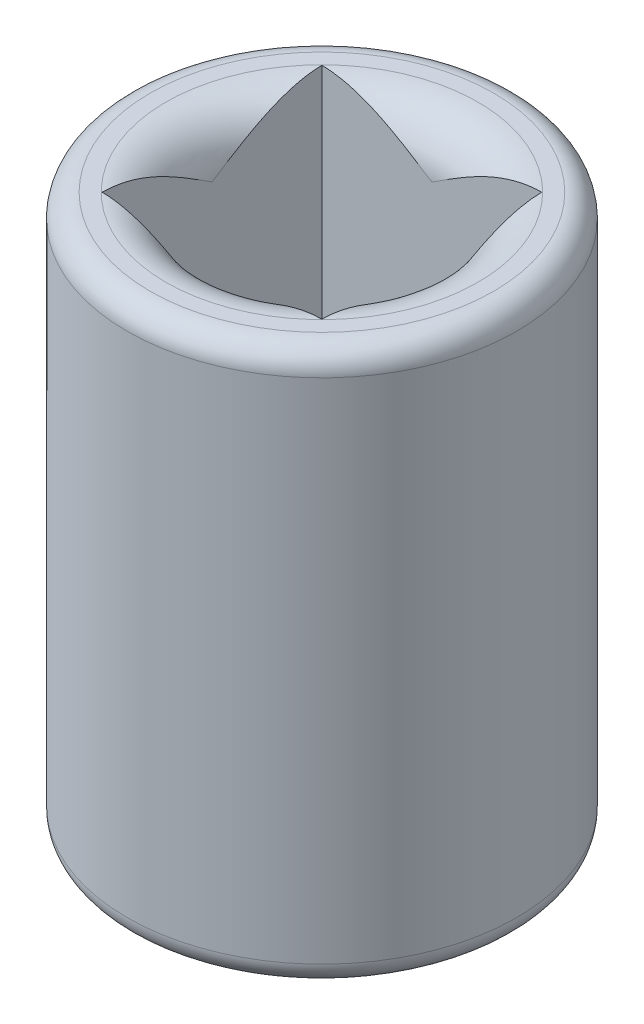
SolidWorks part; units mm, degrees
ref_plane "Front Plane" through (0, 0, 0) normal (0, 0, 1) x (1, 0, 0)
ref_plane "Top Plane" through (0, 0, 0) normal (0, 1, 0) x (1, 0, 0)
ref_plane "Right Plane" through (0, 0, 0) normal (1, 0, 0) x (0, 0, -1)
sketch "Sketch1" plane through (0, 0, 0) normal (0, 1, 0) x (1, 0, 0)
  circle A0 centre (0, 0) radius 8.44
  dimension "D1" = 16.88
extrude "Boss-Extrude1" add sketch "Sketch1" along normal blind 24
sketch "Sketch2" plane through (0, 24, 0) normal (0, 1, 0) x (1, 0, 0)
  line L1 (-4.7625, -4.7625) -> (4.7625, -4.7625)
  line L2 (-4.7625, -4.7625) -> (-4.7625, 4.7625)
  line L3 (-4.7625, 4.7625) -> (4.7625, 4.7625)
  line L4 (4.7625, -4.7625) -> (4.7625, 4.7625)
  line L5 (-4.7625, -4.7625) -> (4.7625, 4.7625) construction
  line L6 (-4.7625, 4.7625) -> (4.7625, -4.7625) construction
  point P0 (0, 0)
  dimension "D1" = 9.525
extrude "Cut-Extrude1" cut sketch "Sketch2" against normal blind 11.44
sketch "Sketch3" plane through (0, 12.56, 0) normal (0, 1, 0) x (1, 0, 0)
  circle A0 centre (0, 0) radius 4.5
  dimension "D1" = 9
extrude "Cut-Extrude2" cut sketch "Sketch3" against normal through all
sketch "Sketch4" plane through (0, 0, 0) normal (0, -1, 0) x (1, 0, 0)
  line L1 (-3.2079, 5.5563) -> (-6.4158, 0)
  line L2 (-6.4158, 0) -> (-3.2079, -5.5562)
  line L3 (-3.2079, -5.5562) -> (3.2079, -5.5562)
  line L4 (3.2079, -5.5562) -> (6.4158, 0)
  line L5 (6.4158, 0) -> (3.2079, 5.5563)
  line L6 (3.2079, 5.5563) -> (-3.2079, 5.5563)
  circle A0 centre (0, 0) radius 5.5562 construction
  dimension "D1" = 11.1125
extrude "Cut-Extrude3" cut sketch "Sketch4" against normal blind 8
sketch "Sketch5" plane through (0, 0, 0) normal (1, 0, 0) x (0, 0, -1)
  line L0 (-5.5563, 8) -> (-5.5563, 0) construction
  line L1 (-8.44, 0) -> (8.44, 0) construction
  line L2 (-6.5563, 0) -> (-5.5563, 0)
  line L3 (-5.5563, 0) -> (-5.5563, 1)
  line L4 (-4.7625, 12.56) -> (-4.7625, 24) construction
  line L5 (8.44, 24) -> (-8.44, 24) construction
  line L6 (-6.7625, 24) -> (-4.7625, 24)
  line L7 (-4.7625, 24) -> (-4.7625, 22)
  arc A0 (-5.5563, 1) -> (-6.5563, 0) centre (-6.5563, 1) cw
  arc A1 (-4.7625, 22) -> (-6.7625, 24) centre (-6.7625, 22) ccw
  dimension "D1" = 1
  dimension "D2" = 2
revolve "Cut-Revolve1" cut sketch "Sketch5" angle 360 about axis through (0, 24, 0) along (0, -1, 0)
fillet "Fillet1" radius 1 2 edges at (0, 0, 8.44) (0, 24, 8.44)
